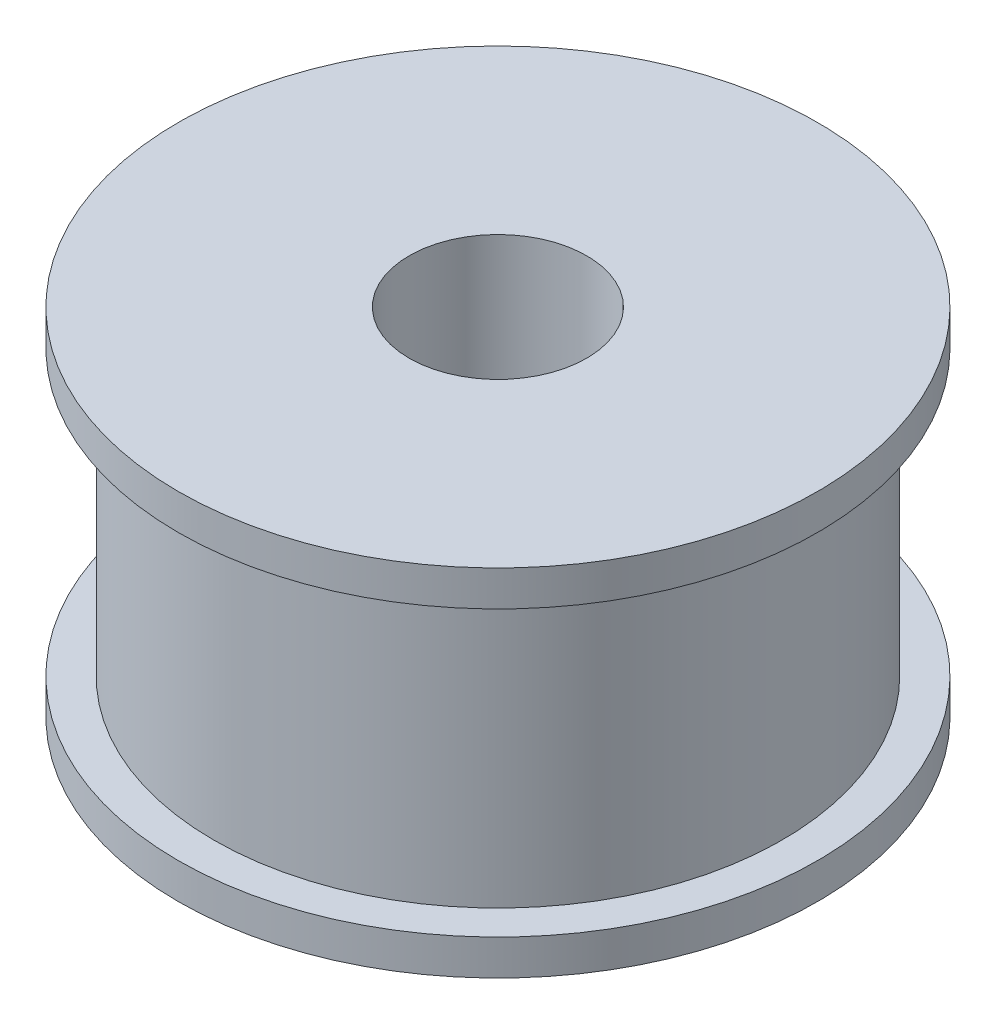
SolidWorks part; units mm, degrees
material "1060 Сплав"
ref_plane "Front" through (0, 0, 0) normal (0, 0, 1) x (1, 0, 0)
ref_plane "Top" through (0, 0, 0) normal (0, 1, 0) x (1, 0, 0)
ref_plane "Right" through (0, 0, 0) normal (1, 0, 0) x (0, 0, -1)
sketch "Эскиз1" plane through (0, 0, 0) normal (0, 1, 0) x (1, 0, 0)
  circle A0 centre (0, 0) radius 2.5
  circle A1 centre (0, 0) radius 9
extrude "Бобышка-Вытянуть1" add sketch "Эскиз1" along normal blind 1
sketch "Эскиз2" plane through (0, 1, 0) normal (0, 1, 0) x (1, 0, 0)
  circle A0 centre (0, 0) radius 2.5
  circle A1 centre (0, 0) radius 8
extrude "Бобышка-Вытянуть2" add sketch "Эскиз2" along normal blind 8
sketch "Эскиз3" plane through (0, 9, 0) normal (0, 1, 0) x (1, 0, 0)
  circle A0 centre (0, 0) radius 2.5
  circle A1 centre (0, 0) radius 9
extrude "Бобышка-Вытянуть3" add sketch "Эскиз3" along normal blind 1
